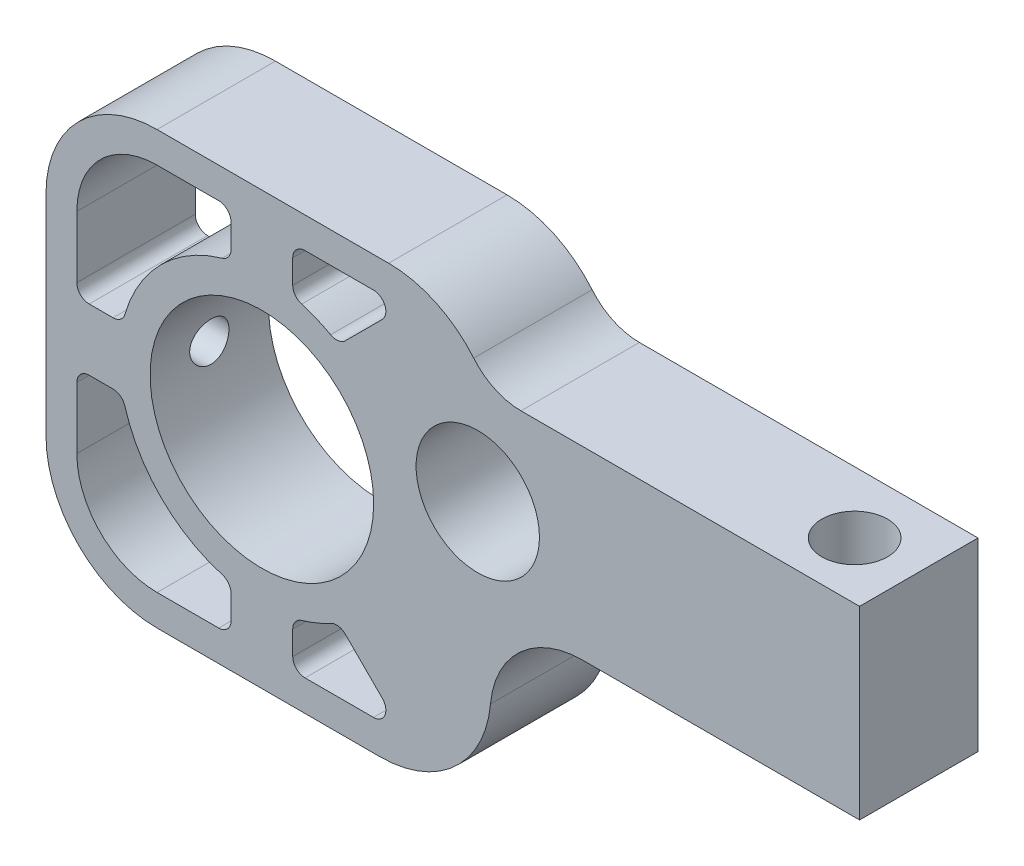
SolidWorks part; units mm, degrees
material "6061 Alloy"
ref_plane "Front Plane" through (0, 0, 0) normal (0, 0, 1) x (1, 0, 0)
ref_plane "Top Plane" through (0, 0, 0) normal (0, 1, 0) x (1, 0, 0)
ref_plane "Right Plane" through (0, 0, 0) normal (1, 0, 0) x (0, 0, -1)
sketch "Sketch1" plane through (0, 0, 0) normal (0, 0, 1) x (1, 0, 0)
  line L1 (0, 0) -> (96.52, 0)
  line L2 (0, 0) -> (0, -44.45)
  line L3 (0, -44.45) -> (96.52, -44.45)
  line L4 (96.52, 0) -> (96.52, -44.45)
  dimension "D1" = 44.45
  dimension "D2" = 96.52
extrude "Boss-Extrude1" add sketch "Sketch1" along normal mid plane 12.192
sketch "Sketch2" plane through (0, 0, 6.096) normal (0, 0, 1) x (1, 0, 0)
  circle A0 centre (22.225, -22.225) radius 11.5087
  dimension "D1" = 23.0175
  dimension "D2" = 22.225
  dimension "D3" = 22.225
extrude "Cut-Extrude1" cut sketch "Sketch2" against normal up to next
sketch "Sketch3" plane through (0, 0, 0) normal (0, 1, 0) x (1, 0, 0)
  line L1 (96.52, 6.096) -> (0, 6.096) construction
  line L2 (96.52, -6.096) -> (96.52, 6.096) construction
  circle A0 centre (77.4065, -0.254) radius 3.3782
  dimension "D1" = 6.7564
  dimension "D2" = 19.1135
  dimension "D3" = 6.35
extrude "Cut-Extrude2" cut sketch "Sketch3" against normal up to next
sketch "Sketch4" plane through (0, 0, 6.096) normal (0, 0, 1) x (1, 0, 0)
  line L0 (48.895, 0) -> (96.52, 0) construction
  line L1 (96.52, 0) -> (0, 0) construction
  line L2 (48.895, 6.35) -> (96.52, 6.35)
  line L3 (48.895, -6.35) -> (96.52, -6.35)
  line L4 (96.52, -34.925) -> (55.245, -34.925) construction
  line L5 (45.72, -34.925) -> (45.72, -44.45)
  line L8 (96.52, -44.45) -> (96.52, 0) construction
  line L9 (96.52, -44.45) -> (55.245, -44.45)
  line L10 (96.52, -25.4) -> (55.245, -25.4)
  line L11 (0, -44.45) -> (96.52, -44.45) construction
  line L12 (45.72, -44.45) -> (55.245, -44.45)
  arc A0 (48.895, 6.35) -> (48.895, -6.35) centre (48.895, 0) ccw
  arc A1 (96.52, -6.35) -> (96.52, 6.35) centre (96.52, 0) ccw
  arc A4 (96.52, -44.45) -> (96.52, -25.4) centre (96.52, -34.925) ccw
  arc A5 (55.245, -25.4) -> (45.72, -34.925) centre (55.245, -34.925) ccw
  point P5 (72.7075, 0)
  dimension "D1" = 6.35
  dimension "D3" = 9.525
  dimension "D2" = 47.625
  dimension "D4" = 41.275
extrude "Cut-Extrude3" cut sketch "Sketch4" against normal up to next
sketch "Sketch7" plane through (0, -6.35, 0) normal (0, 1, 0) x (1, 0, 0)
  line L0 (96.52, 6.096) -> (48.895, 6.096) construction
  line L1 (96.52, -6.096) -> (83.7565, -6.096)
  line L2 (96.52, -6.096) -> (96.52, 6.096)
  line L3 (96.52, 6.096) -> (83.7565, 6.096)
  line L4 (83.7565, -6.096) -> (83.7565, 6.096)
  dimension "D1" = 12.7635
extrude "Cut-Extrude5" cut sketch "Sketch7" against normal through all
fillet "Fillet1" radius 11.43 4 edges at (42.545, 0, 0) (45.72, -44.45, 0) (0, -44.45, 0) (0, 0, 0)
sketch "Sketch11" plane through (0, 0, 0) normal (-1, 0, 0) x (0, 0, 1)
  line L0 (6.096, -11.43) -> (6.096, -33.02) construction
  circle A0 centre (0, -22.225) radius 2.0193
  point P6 (6.096, -22.225)
  dimension "D1" = 4.0386
extrude "Cut-Extrude9" cut sketch "Sketch11" against normal up to next
sketch "Sketch12" plane through (0, 0, 6.096) normal (0, 0, 1) x (1, 0, 0)
  line L0 (17.78, -3.175) -> (11.43, -3.175)
  line L1 (26.67, -41.275) -> (33.7188, -41.275)
  line L2 (32.608, -11.842) -> (39.875, -4.575) construction
  line L3 (39.496, -39.496) -> (32.608, -32.608) construction
  line L5 (34.6168, -5.343) -> (30.8142, -9.1456)
  line L7 (22.225, -7.5413) -> (22.225, -3.175) construction
  line L8 (22.225, -36.9087) -> (22.225, -41.275) construction
  line L9 (7.5413, -22.225) -> (3.175, -22.225) construction
  line L10 (19.05, -6.903) -> (19.05, -4.445)
  line L11 (25.4, -6.903) -> (25.4, -4.445)
  line L12 (4.445, -19.05) -> (6.903, -19.05)
  line L13 (3.175, -11.43) -> (3.175, -33.02)
  line L14 (11.43, -41.275) -> (34.3768, -41.275)
  line L15 (55.245, -22.225) -> (80.5815, -22.225)
  line L16 (80.5815, -22.225) -> (80.5815, -9.525)
  line L17 (80.5815, -9.525) -> (48.895, -9.525)
  line L18 (35.2758, -3.175) -> (11.43, -3.175)
  line L19 (3.175, -11.43) -> (3.175, -17.78)
  line L20 (11.43, -41.275) -> (17.78, -41.275)
  line L24 (33.7188, -3.175) -> (26.67, -3.175)
  line L25 (4.445, -25.4) -> (6.903, -25.4)
  line L26 (25.4, -40.005) -> (25.4, -37.547)
  line L27 (19.05, -40.005) -> (19.05, -37.547)
  line L28 (3.175, -26.67) -> (3.175, -33.02)
  line L29 (34.6168, -39.107) -> (30.8142, -35.3044)
  arc A0 (18.1338, -8.1227) -> (8.1227, -18.1338) centre (22.225, -22.225) ccw
  arc A1 (26.3162, -36.3273) -> (29.3039, -35.0897) centre (22.225, -22.225) ccw
  circle A2 centre (22.225, -22.225) radius 14.6837
  arc A3 (8.1227, -26.3162) -> (18.1338, -36.3273) centre (22.225, -22.225) ccw
  arc A4 (29.3039, -9.3603) -> (26.3162, -8.1227) centre (22.225, -22.225) ccw
  arc A8 (33.7188, -41.275) -> (34.6168, -39.107) centre (33.7188, -40.005) ccw
  arc A9 (30.8142, -35.3044) -> (29.3039, -35.0897) centre (29.9162, -36.2024) ccw
  arc A10 (26.3162, -36.3273) -> (25.4, -37.547) centre (26.67, -37.547) ccw
  arc A11 (26.67, -41.275) -> (25.4, -40.005) centre (26.67, -40.005) cw
  arc A12 (18.1338, -36.3273) -> (19.05, -37.547) centre (17.78, -37.547) cw
  arc A13 (19.05, -40.005) -> (17.78, -41.275) centre (17.78, -40.005) cw
  arc A14 (8.1227, -26.3162) -> (6.903, -25.4) centre (6.903, -26.67) ccw
  arc A15 (4.445, -25.4) -> (3.175, -26.67) centre (4.445, -26.67) ccw
  arc A16 (3.175, -33.02) -> (11.43, -41.275) centre (11.43, -33.02) ccw
  arc A17 (34.3768, -41.275) -> (42.5976, -33.7705) centre (34.3768, -33.02) ccw
  arc A18 (55.245, -22.225) -> (42.5976, -33.7705) centre (55.245, -34.925) ccw
  arc A19 (41.599, -6.1232) -> (48.895, -9.525) centre (48.895, 0) ccw
  arc A20 (41.599, -6.1232) -> (35.2758, -3.175) centre (35.2758, -11.43) ccw
  arc A21 (11.43, -3.175) -> (3.175, -11.43) centre (11.43, -11.43) ccw
  arc A22 (3.175, -33.02) -> (11.43, -41.275) centre (11.43, -33.02) ccw
  arc A27 (11.43, -3.175) -> (3.175, -11.43) centre (11.43, -11.43) ccw
  arc A28 (34.6168, -5.343) -> (33.7188, -3.175) centre (33.7188, -4.445) ccw
  arc A29 (30.8142, -9.1456) -> (29.3039, -9.3603) centre (29.9162, -8.2476) cw
  arc A30 (26.3162, -8.1227) -> (25.4, -6.903) centre (26.67, -6.903) cw
  arc A31 (26.67, -3.175) -> (25.4, -4.445) centre (26.67, -4.445) ccw
  arc A32 (17.78, -3.175) -> (19.05, -4.445) centre (17.78, -4.445) cw
  arc A33 (19.05, -6.903) -> (18.1338, -8.1227) centre (17.78, -6.903) cw
  arc A34 (8.1227, -18.1338) -> (6.903, -19.05) centre (6.903, -17.78) cw
  arc A35 (4.445, -19.05) -> (3.175, -17.78) centre (4.445, -17.78) cw
  circle A36 centre (44.45, -16.6688) radius 6.35
  point P41 (25.4, -36.5614)
  point P45 (25.4, -41.275)
  point P65 (3.175, -25.4)
  point P71 (30.1173, -9.8426)
  point P78 (19.05, -3.175)
  point P81 (19.05, -7.8886)
  point P86 (3.175, -19.05)
  dimension "D11" = 1.27
  dimension "D13" = 12.7
  dimension "D3" = 3.175
  dimension "D4" = 3.175
  dimension "D5" = 3.175
  dimension "D6" = 3.175
  dimension "D7" = 3.175
  dimension "D8" = 3.175
  dimension "D9" = 45
  dimension "D10" = 45
  dimension "D12" = 3.175
  dimension "D14" = 3.175
  dimension "D15" = 22.225
  dimension "D16" = 5.5562
  dimension "D1" = 3.175
  dimension "D2" = 3.175
extrude "Cut-Extrude10" cut sketch "Sketch12" against normal through all
